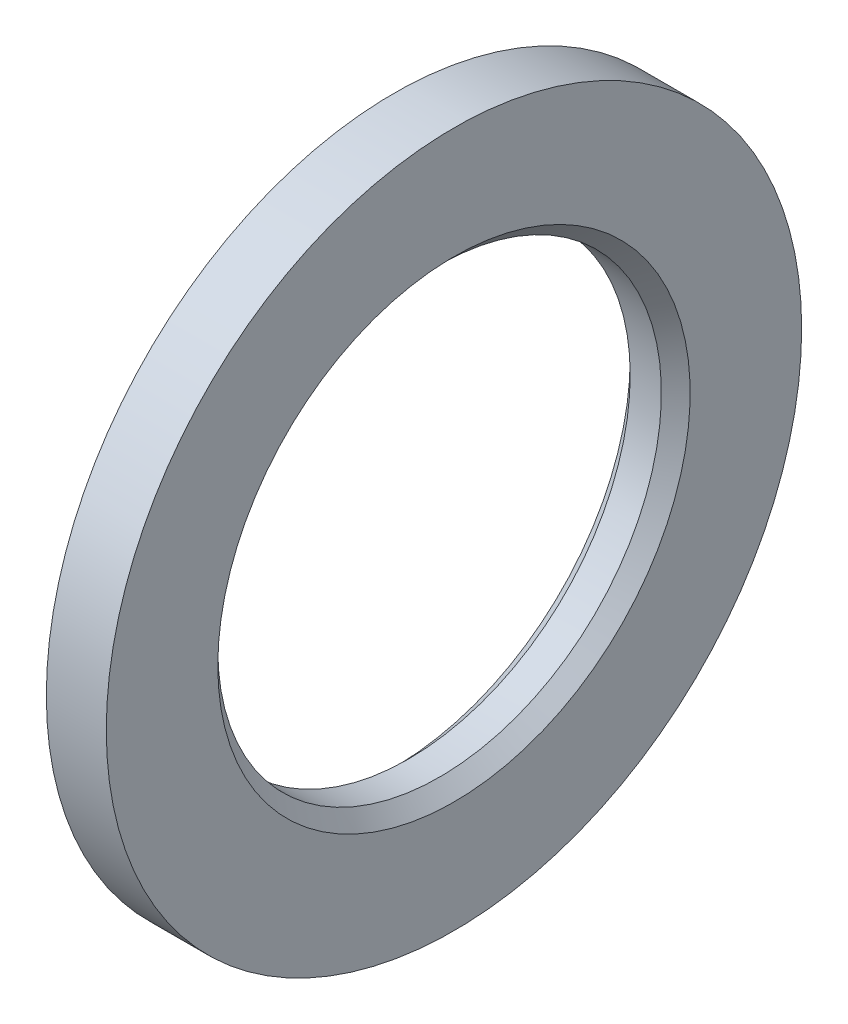
SolidWorks part; units mm, degrees
ref_plane "Plane1" through (0, 0, 0) normal (0, 0, 1) x (1, 0, 0)
ref_plane "Plane2" through (0, 0, 0) normal (0, 1, 0) x (1, 0, 0)
ref_plane "Plane3" through (0, 0, 0) normal (1, 0, 0) x (0, 0, -1)
sketch "Sketch1" plane through (0, 0, 0) normal (0, 0, 1) x (1, 0, 0)
  line L0 (-34.925, 0) -> (9.525, 0) construction
  line L1 (0, 18.5) -> (0, 29)
  line L2 (0, 29) -> (-5, 29)
  line L3 (-5, 29) -> (-5, 18.5)
  line L4 (-5, 18.5) -> (0, 18.5)
  dimension "Thickness" = 5
  dimension "Inside_dia" = 37
  dimension "Outside_dia" = 58
revolve "Base-Revolve" add sketch "Sketch1" angle 360 about L0
chamfer "IDChamfer" distance 1.2 angle 45 1 edges at (0, 0, 18.5)
chamfer "IDChamferFar" distance 1.2 angle 45 1 edges at (-5, 0, 18.5)
equation "\"D1@IDChamferFar\" =  \"Chamfer_width@IDChamfer\""
